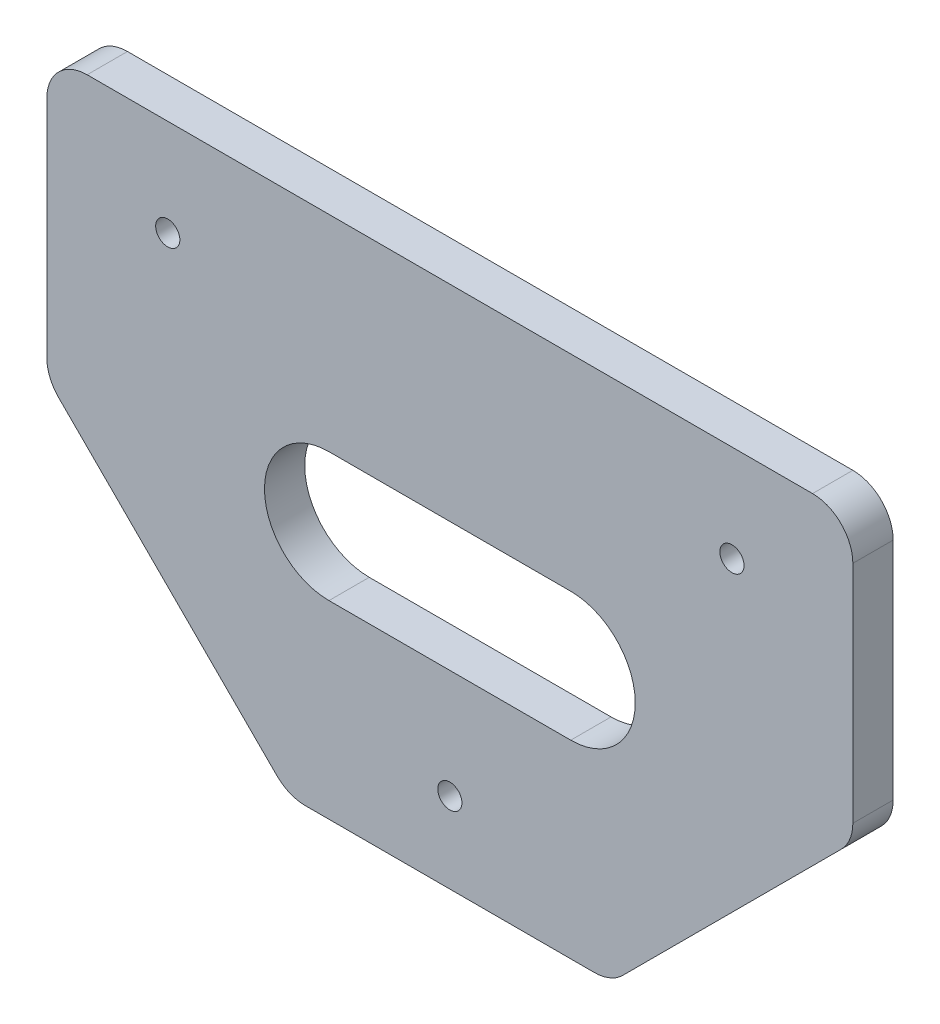
SolidWorks part; units mm, degrees
ref_plane "Front Plane" through (0, 0, 0) normal (0, 0, 1) x (1, 0, 0)
ref_plane "Top Plane" through (0, 0, 0) normal (0, 1, 0) x (1, 0, 0)
ref_plane "Right Plane" through (0, 0, 0) normal (1, 0, 0) x (0, 0, -1)
sketch "Sketch1" plane through (0, 0, 0) normal (0, 0, 1) x (1, 0, 0)
  line L0 (0, 40) -> (30, 10)
  line L1 (30, 10) -> (70, 10)
  line L2 (0, 40) -> (0, 75)
  line L3 (0, 75) -> (100, 75)
  line L4 (100, 40) -> (100, 75)
  line L5 (100, 40) -> (70, 10)
  dimension "D3" = 30
  dimension "D4" = 30
  dimension "D5" = 100
  dimension "D1" = 30
  dimension "D2" = 30
  dimension "D6" = 35
extrude "Boss-Extrude1" add sketch "Sketch1" along normal blind 5
sketch "Sketch3" plane through (0, 0, 5) normal (0, 0, 1) x (1, 0, 0)
  line L5 (0, 75) -> (0, 40) construction
  line L9 (35, 41.5) -> (65, 41.5) construction
  line L10 (35, 49.5) -> (65, 49.5)
  line L11 (35, 33.5) -> (65, 33.5)
  circle A0 centre (50, 20) radius 1.5
  circle A1 centre (85, 63) radius 1.5
  circle A2 centre (15, 63) radius 1.5
  arc A3 (35, 49.5) -> (35, 33.5) centre (35, 41.5) ccw
  arc A4 (65, 33.5) -> (65, 49.5) centre (65, 41.5) ccw
  point P16 (50, 41.5)
  dimension "D1" = 3
  dimension "D2" = 3
  dimension "D3" = 3
  dimension "D17" = 8
  dimension "D4" = 43
  dimension "D5" = 43
  dimension "D6" = 35
  dimension "D12" = 15
  dimension "D13" = 35
  dimension "D14" = 30
  dimension "D15" = 15
  dimension "D16" = 21.5
extrude "Cut-Extrude3" cut sketch "Sketch3" against normal through all
fillet "Fillet1" radius 5 1 edges at (0, 40, 2.5)
fillet "Fillet2" radius 5 1 edges at (100, 40, 2.5)
fillet "Fillet3" radius 5 1 edges at (70, 10, 2.5)
fillet "Fillet4" radius 5 1 edges at (30, 10, 2.5)
fillet "Fillet5" radius 5 1 edges at (100, 75, 2.5)
fillet "Fillet6" radius 5 1 edges at (0, 75, 2.5)
